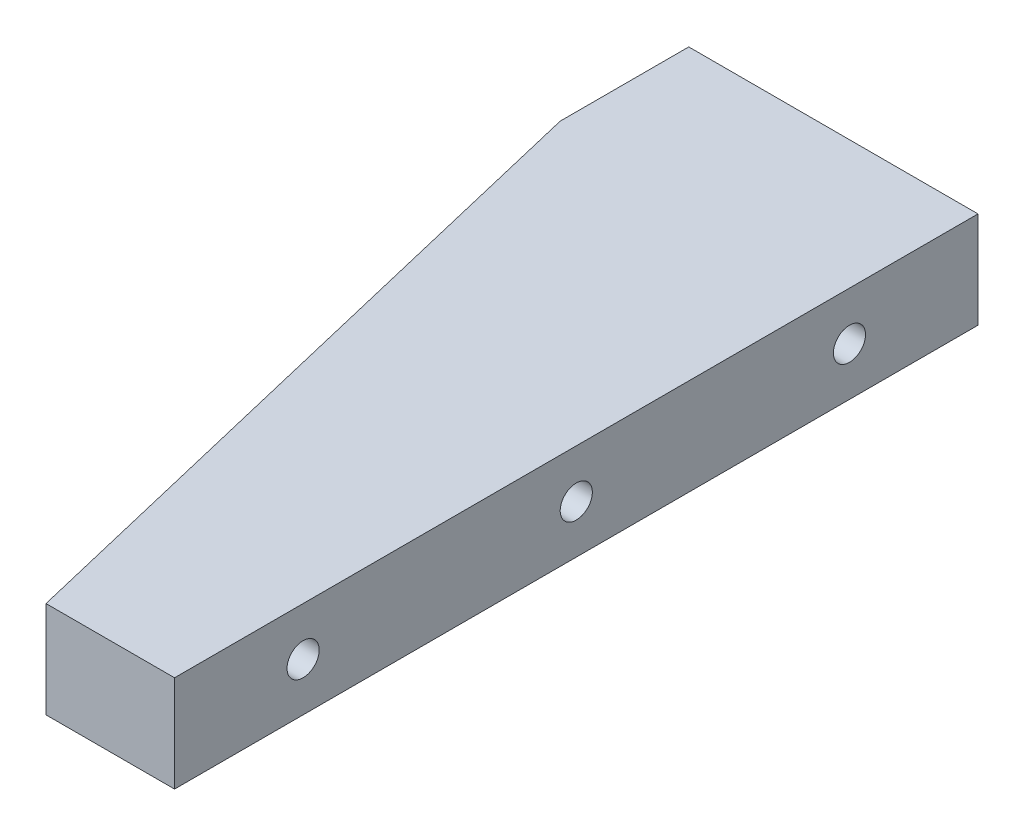
SolidWorks part; units mm, degrees
ref_plane "Front" through (0, 0, 0) normal (0, 0, 1) x (1, 0, 0)
ref_plane "Top" through (0, 0, 0) normal (0, 1, 0) x (1, 0, 0)
ref_plane "Right" through (0, 0, 0) normal (1, 0, 0) x (0, 0, -1)
sketch "Sketch1" plane through (0, 0, 0) normal (0, 1, 0) x (1, 0, 0)
  line L0 (0, 0) -> (0, -125)
  line L1 (0, -125) -> (-20, -125)
  line L2 (-20, -125) -> (-45, -20)
  line L3 (-45, -20) -> (-45, 0)
  line L4 (-45, 0) -> (0, 0)
  dimension "D1" = 125
  dimension "D2" = 45
  dimension "D3" = 20
  dimension "D4" = 20
extrude "Boss-Extrude1" add sketch "Sketch1" along normal blind 15
hole_wizard "M6 Tapped Hole1" positions "Sketch3" profile "Sketch2" tap size "M6" standard "ISO"
sketch "Sketch3" plane through (0, 0, 0) normal (0, 0, -1) x (-1, 0, 0)
  line L0 (0, 15) -> (0, 0) construction
  line L1 (0, 0) -> (45, 0) construction
  point P0 (35, 7.5)
  dimension "D1" = 35
  dimension "D2" = 7.5
sketch "Sketch2" plane through (-35, 7.5, 0) normal (1, 0, 0) x (0, 1, 0)
  line L0 (0, 0) -> (0, 11.5022)
  line L1 (0, 11.5022) -> (2.5, 10)
  line L2 (2.5, 10) -> (2.5, 0)
  line L5 (2.5, 0) -> (0, 0)
  line L10 (0, 11.5022) -> (-2.5, 10) construction
  line L11 (0, -6.35) -> (0, 107.95) construction
  dimension "Tap Drill Dia." = 5
  dimension "Tap Drill Depth" = 10
  dimension "Drill Angle" = 118
cosmetic thread "Hole Thread1"
hole_wizard "M6 Tapped Hole2" positions "Sketch5" profile "Sketch4" tap size "M6" standard "ISO"
sketch "Sketch5" plane through (0, 0, 0) normal (1, 0, 0) x (0, 0, -1)
  line L0 (0, 15) -> (0, 0) construction
  line L1 (-125, 0) -> (0, 0) construction
  point P0 (-105, 7.5)
  point P1 (-62.5, 7.5)
  point P3 (-20, 7.5)
  dimension "D1" = 20
  dimension "D2" = 42.5
  dimension "D3" = 42.5
  dimension "D4" = 7.5
sketch "Sketch4" plane through (0, 7.5, 105) normal (0, 1, 0) x (0, 0, -1)
  line L0 (0, 0) -> (0, 11.5022)
  line L1 (0, 11.5022) -> (2.5, 10)
  line L2 (2.5, 10) -> (2.5, 0)
  line L5 (2.5, 0) -> (0, 0)
  line L10 (0, 11.5022) -> (-2.5, 10) construction
  line L11 (0, -6.35) -> (0, 107.95) construction
  dimension "Tap Drill Dia." = 5
  dimension "Tap Drill Depth" = 10
  dimension "Drill Angle" = 118
cosmetic thread "Hole Thread2"
cosmetic thread "Hole Thread3"
cosmetic thread "Hole Thread4"
